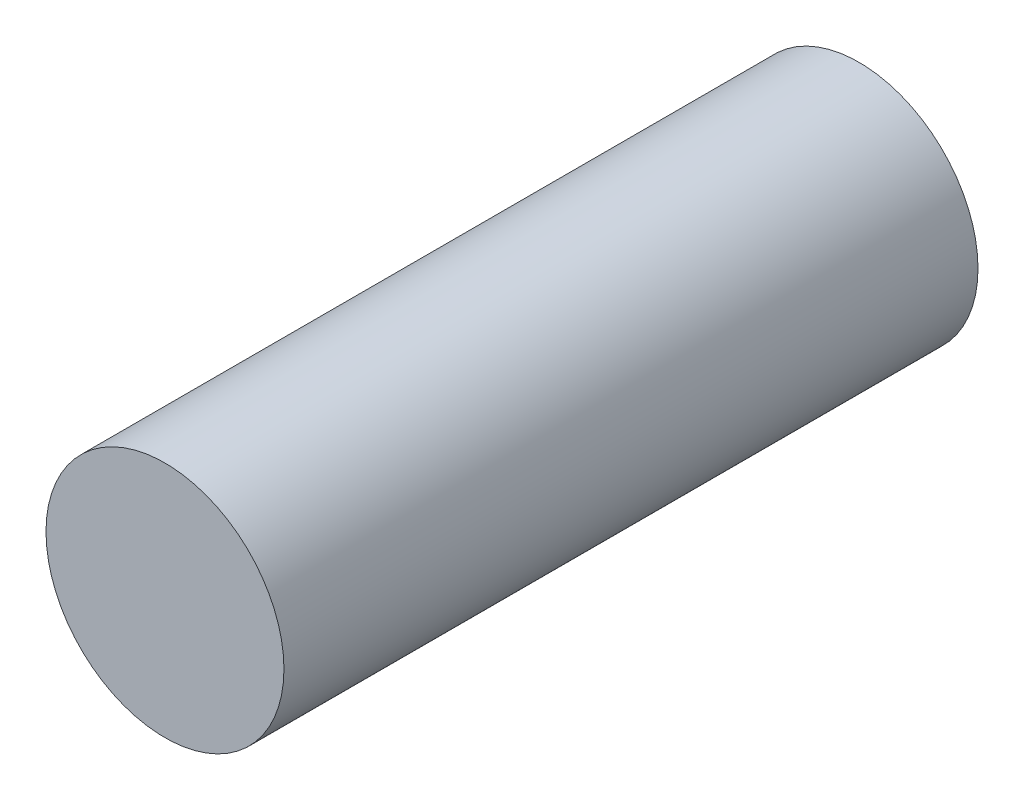
SolidWorks part; units mm, degrees
ref_plane "Front" through (0, 0, 0) normal (0, 0, 1) x (1, 0, 0)
ref_plane "Top" through (0, 0, 0) normal (0, 1, 0) x (1, 0, 0)
ref_plane "Right" through (0, 0, 0) normal (1, 0, 0) x (0, 0, -1)
sketch "草图1" plane through (0, 0, 0) normal (0, 0, 1) x (1, 0, 0)
  circle A0 centre (0, 0) radius 30
  dimension "D1" = 60
extrude "凸台-拉伸1" add sketch "草图1" along normal blind 175
